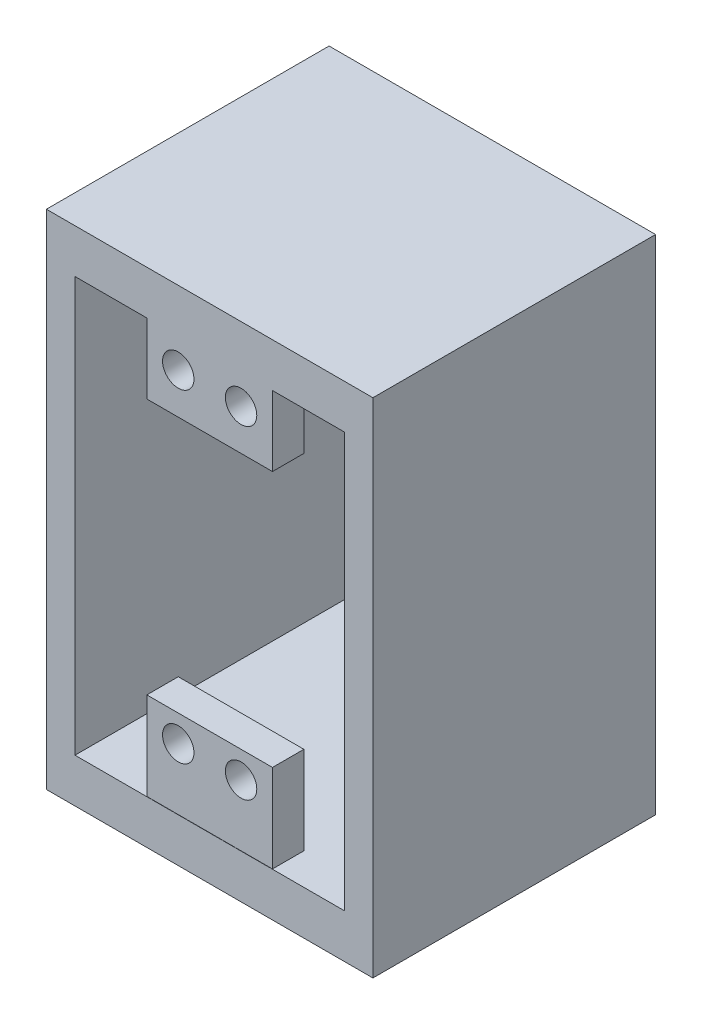
SolidWorks part; units mm, degrees
ref_plane "Ebene vorne" through (0, 0, 0) normal (0, 0, 1) x (1, 0, 0)
ref_plane "Ebene oben" through (0, 0, 0) normal (0, 1, 0) x (1, 0, 0)
ref_plane "Ebene rechts" through (0, 0, 0) normal (1, 0, 0) x (0, 0, -1)
sketch "Skizze1" plane through (0, 0, 0) normal (0, 0, 1) x (1, 0, 0)
  line L0 (-20, 54.79) -> (-20, 65.97)
  line L1 (0, 0) -> (-20, 0)
  line L2 (0, 0) -> (0, 14)
  line L3 (0, 65.97) -> (-20, 65.97)
  line L4 (-20, 0) -> (-20, 14)
  line L7 (-20, 54.79) -> (0, 54.79)
  line L8 (0, 65.97) -> (0, 54.79)
  line L11 (-20, 14) -> (0, 14)
  circle A0 centre (-15, 61.2768) radius 2.5
  circle A1 centre (-5, 61.2768) radius 2.5
  circle A2 centre (-15, 9.7612) radius 2.5
  circle A3 centre (-5, 9.7612) radius 2.5
  point P19 (-76.0969, 56.7282)
  dimension "D5" = 5
  dimension "D6" = 5
  dimension "D9" = 5
  dimension "D10" = 5
  dimension "D1" = 20
  dimension "D2" = 65.97
  dimension "D3" = 11.18
  dimension "D4" = 14
  dimension "D7" = 10
  dimension "D8" = 5
  dimension "D11" = 10
  dimension "D12" = 5
extrude "Aufsatz-Linear austragen1" add sketch "Skizze1" along normal blind 5
sketch "Skizze3" plane through (0, 0, 5) normal (0, 0, 1) x (1, 0, 0)
  line L0 (0, 72.962) -> (0, 92.6347) construction
  line L1 (-20, 65.97) -> (0, 65.97) construction
  line L2 (0, 65.97) -> (-10, 65.97) construction
  line L4 (-10, 65.97) -> (-10, 65.962) construction
  line L6 (11.44, 32.962) -> (11.6858, 32.962) construction
  line L7 (11.6858, 32.962) -> (11.44, 32.962) construction
  line L8 (-31.44, 32.962) -> (-37.4219, 32.962) construction
  line L9 (-35.9879, 72.962) -> (15.9879, 72.962)
  line L10 (-35.9879, 72.962) -> (-35.9879, -7.038)
  line L11 (-35.9879, -7.038) -> (15.9879, -7.038)
  line L12 (15.9879, 72.962) -> (15.9879, -7.038)
  line L15 (-31.44, 65.962) -> (11.44, 65.962)
  line L16 (-31.44, 65.962) -> (-31.44, -0.038)
  line L17 (-31.44, -0.038) -> (11.44, -0.038)
  line L18 (11.44, 65.962) -> (11.44, -0.038)
  line L21 (11.44, 65.962) -> (15.9879, 72.962) construction
  line L23 (0, 65.962) -> (0, 65.97) construction
  dimension "D1" = 80
  dimension "D2" = 66
extrude "Aufsatz-Linear austragen2" add sketch "Skizze3" against normal blind 45
sketch "Skizze5" plane through (0, 0, 5) normal (0, 0, 1) x (1, 0, 0)
  line L0 (-10, -7.038) -> (-10, 34.2424) construction
  line L1 (-35.9879, -7.038) -> (15.9879, -7.038) construction
  line L2 (-15, 9.7612) -> (-5, 9.7612) construction
  line L3 (-5, 9.7612) -> (-39.9489, 9.7612) construction
  line L4 (-39.9489, 9.7612) -> (18.9388, 9.7612) construction
  circle A0 centre (-10, 20.1105) radius 10
  dimension "D1" = 20
